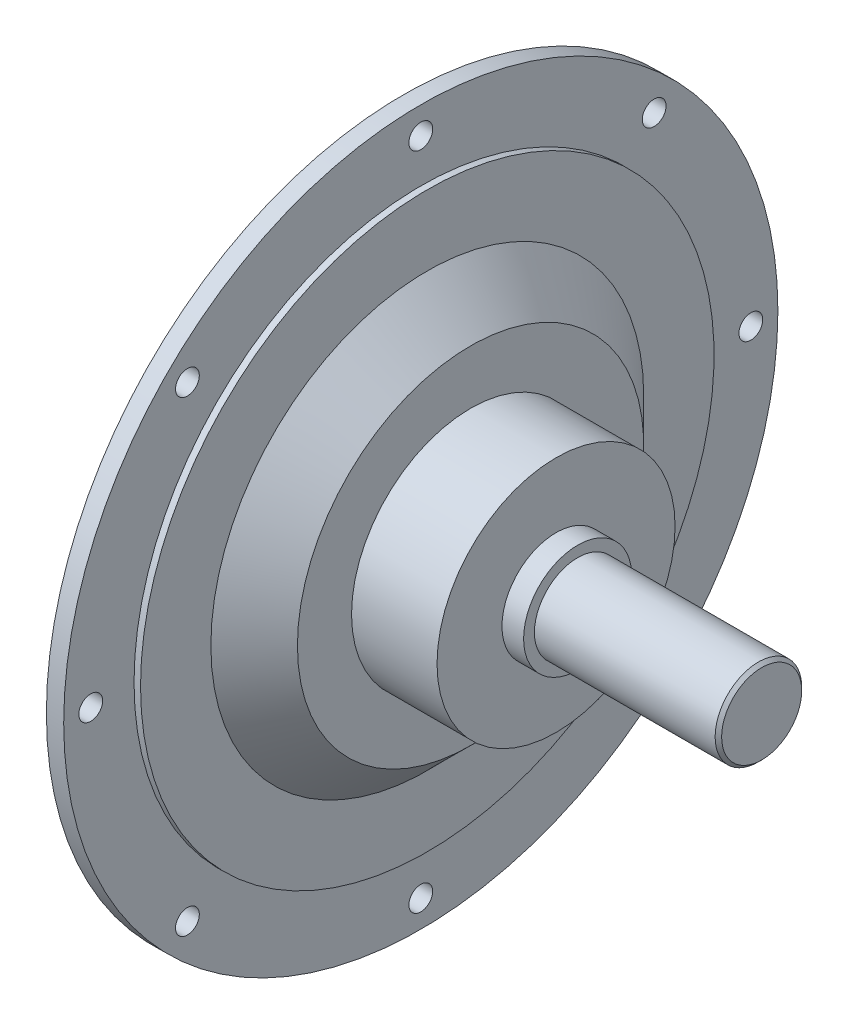
SolidWorks part; units mm, degrees
ref_plane "Vorderansicht" through (0, 0, 0) normal (0, 0, 1) x (1, 0, 0)
ref_plane "Draufsicht" through (0, 0, 0) normal (0, 1, 0) x (1, 0, 0)
ref_plane "Seitenansicht" through (0, 0, 0) normal (1, 0, 0) x (0, 0, -1)
sketch "Skizze3" plane through (0, 0, 0) normal (0, 0, 1) x (1, 0, 0)
  line L0 (-57.655, 0) -> (233.1421, 0) construction
  line L1 (0, 132.5) -> (0, 165)
  line L2 (0, 165) -> (-8, 165)
  line L3 (-8, 165) -> (-8, 95.4437)
  line L4 (0, 132.5) -> (3, 132.5)
  line L5 (3, 132.5) -> (3, 100)
  line L6 (3, 100) -> (23, 80)
  line L7 (23, 80) -> (23, 55)
  line L8 (23, 55) -> (62.5, 55)
  line L9 (62.5, 55) -> (62.5, 25)
  line L10 (157.5, 0) -> (-40, 0)
  line L11 (-40, 0) -> (-40, 55)
  line L12 (-40, 55) -> (12, 68.9334)
  line L13 (-8, 95.4437) -> (12, 75.4437)
  line L14 (12, 75.4437) -> (12, 68.9334)
  line L15 (-4.7782, 92.2218) -> (12, 75.4437) construction
  line L16 (62.5, 25) -> (72.5, 25)
  line L17 (12, 75.4437) -> (12, 55) construction
  line L18 (72.5, 25) -> (72.5, 20)
  line L19 (72.5, 20) -> (157.5, 20)
  line L20 (157.5, 20) -> (157.5, 0)
  dimension "D1" = 330
  dimension "D2" = 8
  dimension "D3" = 3
  dimension "D4" = 265
  dimension "D5" = 62.5
  dimension "D6" = 110
  dimension "D7" = 160
  dimension "D8" = 45
  dimension "D9" = 20
  dimension "D11" = 32
  dimension "D12" = 75
  dimension "D13" = 197.5
  dimension "D14" = 85
  dimension "D15" = 40
  dimension "D16" = 50
  dimension "D10" = 11
revolve "Rotation1" add sketch "Skizze3" angle 360 about L0
chamfer "Fase1" distance 1.5 angle 45 1 edges at (157.5, 0, 20)
hole_wizard "Durchgangsloch für M101" positions "Skizze5" profile "Skizze4" hole size "M10" standard "DIN" end condition up to next
sketch "Skizze5" plane through (0, 0, 0) normal (1, 0, 0) x (0, 0, -1)
  point P0 (0, 152.5)
  dimension "D1" = 152.5
sketch "Skizze4" plane through (0, 152.5, 0) normal (0, 1, 0) x (0, 0, -1)
  line L0 (0, 0) -> (0, 8.001)
  line L1 (0, 8.001) -> (5.5, 8.001)
  line L2 (5.5, 8.001) -> (5.5, 0)
  line L5 (5.5, 0) -> (0, 0)
  line L11 (0, -6.35) -> (0, 107.95) construction
  dimension "Bohrerdurchmesser" = 11
  dimension "Bohrungstiefe" = 8.001
pattern_circular "Kreismuster1" count 8 over 360 about axis through (0, 0, 0) along (1, 0, 0) of "Durchgangsloch für M101"
